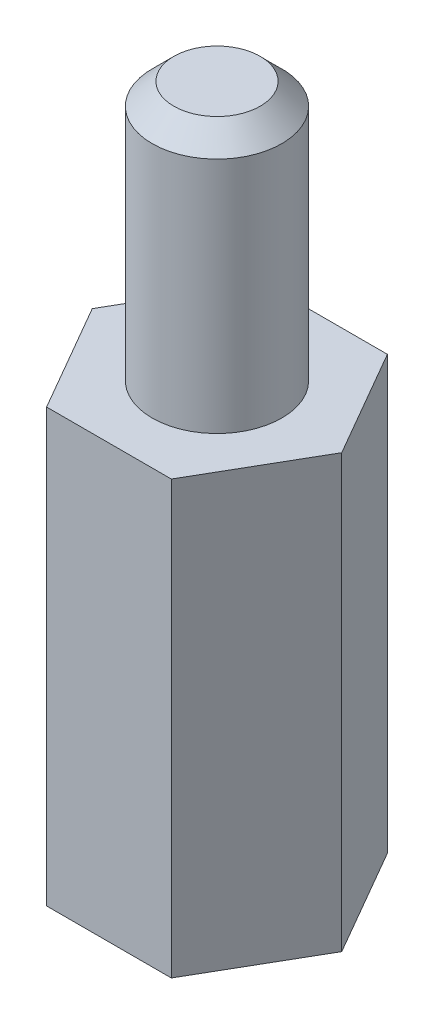
SolidWorks part; units mm, degrees
ref_plane "Спереди" through (0, 0, 0) normal (0, 0, 1) x (1, 0, 0)
ref_plane "Сверху" through (0, 0, 0) normal (0, 1, 0) x (1, 0, 0)
ref_plane "Справа" through (0, 0, 0) normal (1, 0, 0) x (0, 0, -1)
sketch "Эскиз1" plane through (0, 0, 0) normal (0, 1, 0) x (1, 0, 0)
  line L1 (1.4434, -2.5) -> (2.8868, 0)
  line L2 (2.8868, 0) -> (1.4434, 2.5)
  line L3 (1.4434, 2.5) -> (-1.4434, 2.5)
  line L4 (-1.4434, 2.5) -> (-2.8868, 0)
  line L5 (-2.8868, 0) -> (-1.4434, -2.5)
  line L6 (-1.4434, -2.5) -> (1.4434, -2.5)
  circle A0 centre (0, 0) radius 2.5 construction
  dimension "D1" = 5
extrude "Бобышка-Вытянуть1" add sketch "Эскиз1" along normal blind 10
hole_wizard "Диаметр отверстия Ø3.0 (3)1" positions "Эскиз2" profile "Эскиз3" hole size "Ø3.0" standard "Ansi Metric"
sketch "Эскиз2" plane through (0, 0, 0) normal (0, -1, 0) x (-1, 0, 0)
  point P0 (0, 0)
sketch "Эскиз3" plane through (0, 0, 0) normal (1, 0, 0) x (0, 0, -1)
  line L0 (0, 0) -> (0, 9.4013)
  line L1 (0, 9.4013) -> (1.5, 8.5)
  line L2 (1.5, 8.5) -> (1.5, 0)
  line L5 (1.5, 0) -> (0, 0)
  line L10 (0, 9.4013) -> (-1.5, 8.5) construction
  line L11 (0, -6.35) -> (0, 107.95) construction
  dimension "Диаметр отверстия" = 3
  dimension "Глубина отверстия" = 8.5
  dimension "Угол заточки сверла" = 118
sketch "Эскиз4" plane through (0, 10, 0) normal (0, 1, 0) x (1, 0, 0)
  circle A0 centre (0, 0) radius 1.5
  dimension "D1" = 3
extrude "Бобышка-Вытянуть2" add sketch "Эскиз4" along normal blind 6
cosmetic thread "Условное изображение резьбы1" parameters "D2"=2.439
chamfer "Фаска1" distance 0.5 angle 45 2 edges at (0, 16, 1.5) (0, 0, -1.5)
ref_point "Точка2"
